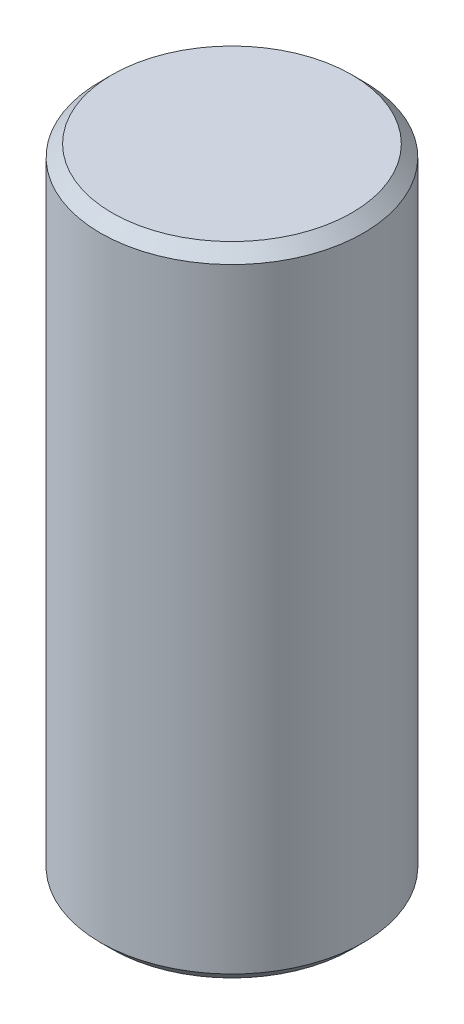
SolidWorks part; units mm, degrees
ref_plane "Plano frontal" through (0, 0, 0) normal (0, 0, 1) x (1, 0, 0)
ref_plane "Plano superior" through (0, 0, 0) normal (0, 1, 0) x (1, 0, 0)
ref_plane "Plano direito" through (0, 0, 0) normal (1, 0, 0) x (0, 0, -1)
sketch "Esboço1" plane through (0, 0, 0) normal (0, 1, 0) x (1, 0, 0)
  circle A0 centre (0, 0) radius 16.9
  dimension "D1" = 33.8
extrude "Ressalto-extrusão1" add sketch "Esboço1" along normal blind 82
chamfer "Chanfro1" distance 1.5 angle 45 2 edges at (0, 0, 16.9) (0, 82, 16.9)
